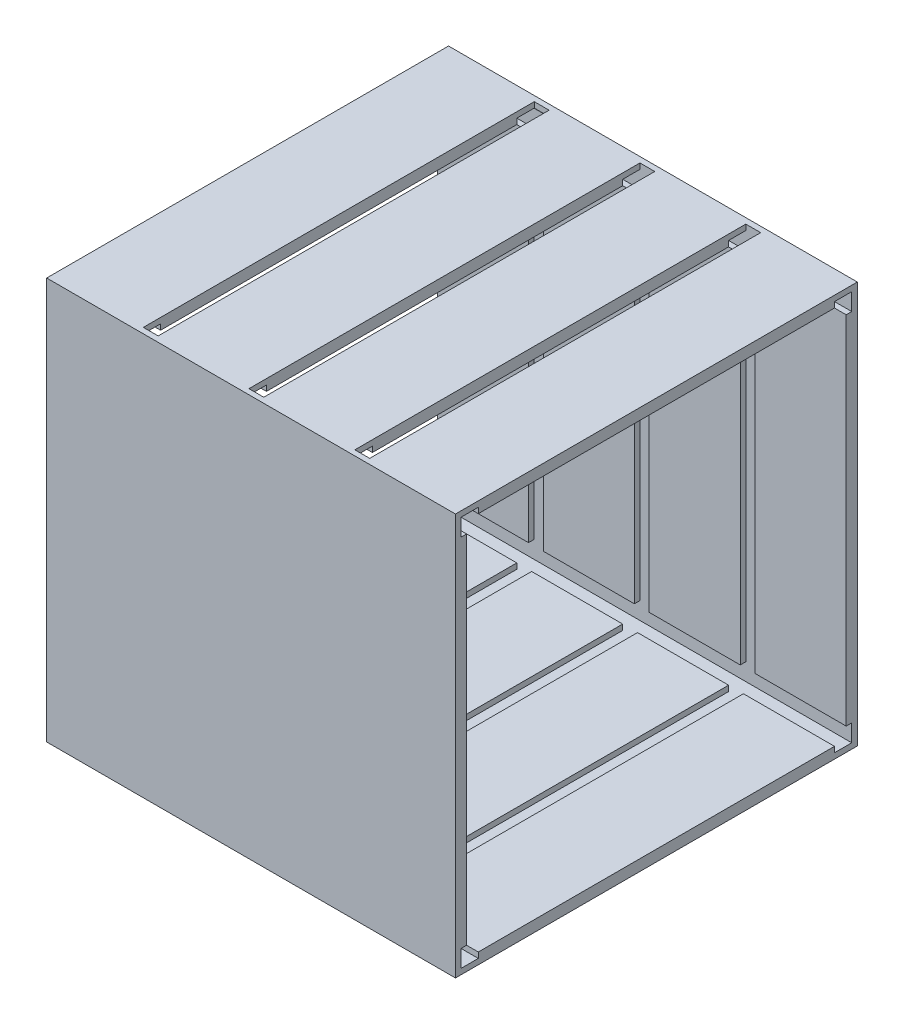
SolidWorks part; units mm, degrees
ref_plane "Front Plane" through (0, 0, 0) normal (0, 0, 1) x (1, 0, 0)
ref_plane "Top Plane" through (0, 0, 0) normal (0, 1, 0) x (1, 0, 0)
ref_plane "Right Plane" through (0, 0, 0) normal (1, 0, 0) x (0, 0, -1)
sketch "Sketch1" plane through (0, 0, 0) normal (1, 0, 0) x (0, 0, -1)
  line L1 (0, 0) -> (688.1, 0)
  line L2 (0, 0) -> (0, 688.1)
  line L3 (0, 688.1) -> (688.1, 688.1)
  line L4 (688.1, 0) -> (688.1, 688.1)
  line L5 (0, 0) -> (19.05, 0) construction
  line L6 (0, 0) -> (0, 19.05) construction
  line L7 (0, 19.05) -> (19.05, 19.05) construction
  line L8 (19.05, 0) -> (19.05, 19.05) construction
  line L9 (19.05, 19.05) -> (669.05, 19.05)
  line L10 (19.05, 19.05) -> (19.05, 669.05)
  line L11 (19.05, 669.05) -> (669.05, 669.05)
  line L12 (669.05, 19.05) -> (669.05, 669.05)
  dimension "D1" = 688.1
  dimension "D2" = 688.1
  dimension "D3" = 19.05
  dimension "D4" = 19.05
  dimension "D5" = 650
  dimension "D6" = 650
extrude "Boss-Extrude1" add sketch "Sketch1" along normal blind 700 contours L10 L11 L12 L9 | L2 L3 L4 L1
sketch "Sketch3" plane through (0, 0, -669.05) normal (0, 0, 1) x (1, 0, 0)
  line L1 (0, 669.05) -> (155.95, 669.05) construction
  line L2 (0, 669.05) -> (0, 19.05) construction
  line L3 (0, 19.05) -> (155.95, 19.05) construction
  line L4 (155.95, 669.05) -> (155.95, 19.05) construction
  line L5 (155.95, 669.05) -> (181.35, 669.05)
  line L6 (155.95, 669.05) -> (155.95, 19.05)
  line L7 (155.95, 19.05) -> (181.35, 19.05)
  line L8 (181.35, 669.05) -> (181.35, 19.05)
  line L9 (337.3, 669.05) -> (362.7, 669.05)
  line L10 (337.3, 669.05) -> (337.3, 19.05)
  line L11 (337.3, 19.05) -> (362.7, 19.05)
  line L12 (362.7, 669.05) -> (362.7, 19.05)
  line L13 (518.65, 669.05) -> (544.05, 669.05)
  line L14 (518.65, 669.05) -> (518.65, 19.05)
  line L15 (518.65, 19.05) -> (544.05, 19.05)
  line L16 (544.05, 669.05) -> (544.05, 19.05)
  line L17 (700, 688.1) -> (0, 688.1) construction
  point P15 (350, 669.05)
  dimension "D1" = 155.95
  dimension "D2" = 650
  dimension "D3" = 25.4
  dimension "D4" = 25.4
  dimension "D5" = 650
  dimension "D6" = 155.95
  dimension "D7" = 25.4
  dimension "D8" = 650
  dimension "D9" = 155.95
  dimension "D10" = 19.05
  dimension "D11" = 19.05
extrude "Cut-Extrude1" cut sketch "Sketch3" against normal blind 9.525
ref_plane "Plane1" through (0, 0, -344.05) normal (0, 0, -1) x (-1, 0, 0)
mirror "Mirror2" about plane through (0, 0, -344.05) normal (0, 0, -1) of "Cut-Extrude1"
ref_plane "Plane2" through (0, 344.05, 0) normal (0, 1, 0) x (1, 0, 0)
sketch "Sketch4" plane through (0, 19.05, 0) normal (0, 1, 0) x (1, 0, 0)
  line L0 (700, 688.1) -> (0, 688.1) construction
  line L1 (155.95, 678.575) -> (181.35, 678.575)
  line L2 (155.95, 678.575) -> (155.95, 9.075)
  line L3 (155.95, 9.075) -> (181.35, 9.075)
  line L4 (181.35, 678.575) -> (181.35, 9.075)
  line L5 (0, 0) -> (0, 688.1) construction
  line L6 (700, 0) -> (0, 0) construction
  line L7 (337.3, 678.575) -> (362.7, 678.575)
  line L8 (337.3, 678.575) -> (337.3, 9.075)
  line L9 (337.3, 9.075) -> (362.7, 9.075)
  line L10 (362.7, 678.575) -> (362.7, 9.075)
  line L11 (518.65, 678.575) -> (544.05, 678.575)
  line L12 (518.65, 678.575) -> (518.65, 9.525)
  line L13 (518.65, 9.525) -> (544.05, 9.525)
  line L14 (544.05, 678.575) -> (544.05, 9.525)
  dimension "D1" = 25.4
  dimension "D2" = 669.5
  dimension "D3" = 9.525
  dimension "D4" = 155.95
  dimension "D5" = 669.5
  dimension "D6" = 25.4
  dimension "D7" = 9.525
  dimension "D8" = 155.95
  dimension "D9" = 25.4
  dimension "D10" = 155.95
  dimension "D11" = 9.525
  dimension "D12" = 9.525
extrude "Cut-Extrude3" cut sketch "Sketch4" against normal blind 9.525
mirror "Mirror4" about plane through (0, 344.05, 0) normal (0, 1, 0) of "Cut-Extrude3"
sketch "Sketch6" plane through (0, 688.1, 0) normal (0, 1, 0) x (1, 0, 0)
  line L0 (0, 0) -> (0, 688.1) construction
  line L1 (155.95, 679.025) -> (181.35, 679.025)
  line L2 (155.95, 679.025) -> (155.95, 9.525)
  line L3 (155.95, 9.525) -> (181.35, 9.525)
  line L4 (181.35, 679.025) -> (181.35, 9.525)
  line L5 (337.3, 678.575) -> (362.7, 678.575)
  line L6 (337.3, 678.575) -> (337.3, 9.075)
  line L7 (337.3, 9.075) -> (362.7, 9.075)
  line L8 (362.7, 678.575) -> (362.7, 9.075)
  line L9 (518.65, 678.575) -> (544.05, 678.575)
  line L10 (518.65, 678.575) -> (518.65, 9.075)
  line L11 (518.65, 9.075) -> (544.05, 9.075)
  line L12 (544.05, 678.575) -> (544.05, 9.075)
  line L13 (700, 0) -> (0, 0) construction
  line L14 (700, 688.1) -> (0, 688.1) construction
  dimension "D1" = 669.5
  dimension "D2" = 25.4
  dimension "D3" = 155.95
  dimension "D4" = 9.525
  dimension "D5" = 25.4
  dimension "D6" = 669.5
  dimension "D7" = 9.525
  dimension "D8" = 155.95
  dimension "D9" = 25.4
  dimension "D10" = 669.5
  dimension "D11" = 9.525
  dimension "D12" = 155.95
extrude "Cut-Extrude4" cut sketch "Sketch6" against normal blind 9.525
sketch "Sketch7" plane through (0, 0, 0) normal (-1, 0, 0) x (0, 0, 1)
  line L0 (-19.05, 39.05) -> (-9.525, 39.05)
  line L1 (-19.05, 19.05) -> (-19.05, 669.05) construction
  line L2 (-9.525, 39.05) -> (-9.525, 9.525)
  line L3 (-9.525, 9.525) -> (-39.05, 9.525)
  line L4 (-39.05, 9.525) -> (-39.05, 19.05)
  line L5 (-19.05, 19.05) -> (-669.05, 19.05) construction
  line L6 (-39.05, 19.05) -> (-19.05, 19.05)
  line L7 (-19.05, 19.05) -> (-19.05, 39.05)
  dimension "D1" = 9.525
  dimension "D2" = 20
  dimension "D3" = 20
  dimension "D4" = 9.525
extrude "Cut-Extrude5" cut sketch "Sketch7" against normal blind 700
mirror "Mirror5" about plane through (0, 0, -344.05) normal (0, 0, -1) of "Cut-Extrude5"
mirror "Mirror6" about plane through (0, 344.05, 0) normal (0, 1, 0) of "Mirror5", "Cut-Extrude5"
